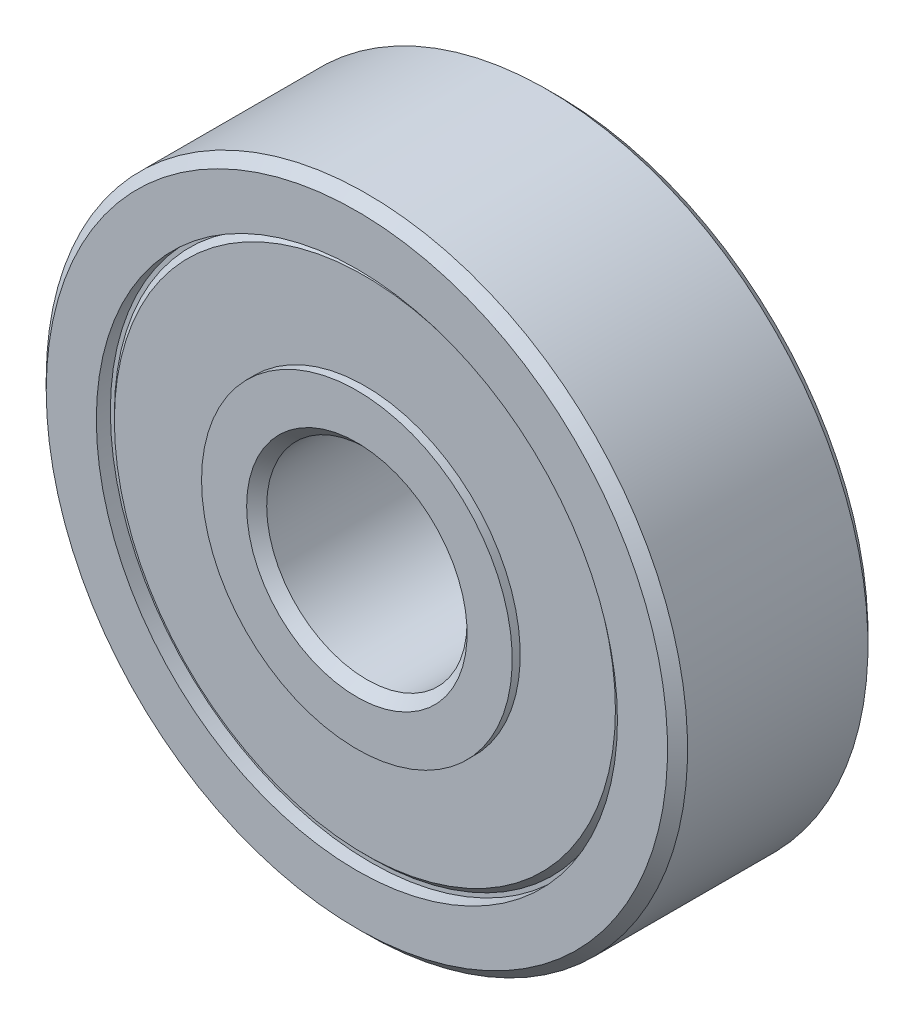
SolidWorks part; units mm, degrees
ref_plane "Front" through (0, 0, 0) normal (0, 0, 1) x (1, 0, 0)
ref_plane "Top" through (0, 0, 0) normal (0, 1, 0) x (1, 0, 0)
ref_plane "Right" through (0, 0, 0) normal (1, 0, 0) x (0, 0, -1)
sketch "Sketch1" plane through (0, 0, 0) normal (0, 1, 0) x (1, 0, 0)
  line L0 (0, 5.3457) -> (0, 0) construction
  line L1 (0, 0) -> (9.6698, 0) construction
  line L2 (2.5, -2.25) -> (2.5, 2.25)
  line L3 (2.5, 2.25) -> (2.75, 2.5)
  line L4 (2.75, 2.5) -> (3.875, 2.5)
  line L5 (3.875, 2.5) -> (3.875, 2.3)
  line L6 (3.875, 2.3) -> (6.25, 2.3)
  line L7 (6.25, 2.3) -> (6.4, 2.15)
  line L8 (6.4, 2.15) -> (6.5, 2.15)
  line L9 (6.5, 2.15) -> (6.5, 2.5)
  line L10 (6.5, 2.5) -> (7.75, 2.5)
  line L11 (7.75, 2.5) -> (8, 2.25)
  line L12 (8, 2.25) -> (8, -2.25)
  line L13 (7.75, -2.5) -> (8, -2.25)
  line L32 (6.5, -2.5) -> (7.75, -2.5)
  line L33 (6.5, -2.15) -> (6.5, -2.5)
  line L34 (6.4, -2.15) -> (6.5, -2.15)
  line L35 (6.25, -2.3) -> (6.4, -2.15)
  line L36 (3.875, -2.5) -> (3.875, -2.3)
  line L37 (3.875, -2.3) -> (6.25, -2.3)
  line L38 (2.75, -2.5) -> (3.875, -2.5)
  line L39 (2.5, -2.25) -> (2.75, -2.5)
  dimension "D1" = 5
  dimension "D2" = 5
  dimension "D3" = 16
  dimension "D4" = 1.375
  dimension "D5" = 1.5
  dimension "D6" = 0.2
  dimension "D7" = 0.35
  dimension "D8" = 0.1
  dimension "D9" = 45
  dimension "D10" = 0.25
revolve "Revolve1" add sketch "Sketch1" angle 360 about L0
